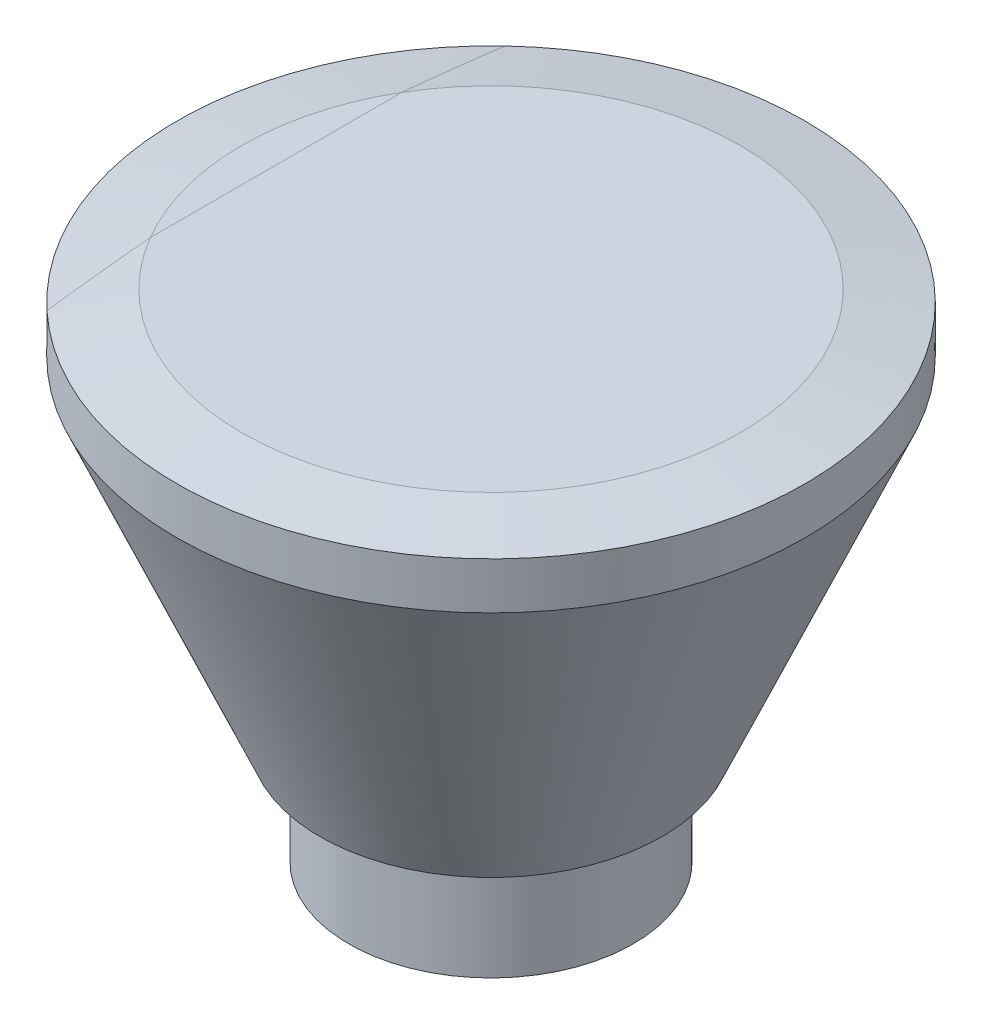
SolidWorks part; units mm, degrees
material "PLA"
ref_plane "Front Plane" through (0, 0, 0) normal (0, 0, 1) x (1, 0, 0)
ref_plane "Top Plane" through (0, 0, 0) normal (0, 1, 0) x (1, 0, 0)
ref_plane "Right Plane" through (0, 0, 0) normal (1, 0, 0) x (0, 0, -1)
sketch "Sketch1" plane through (0, 0, 0) normal (0, 0, 1) x (1, 0, 0)
  line L0 (-19, 22.4817) -> (-15.0608, 23.1763)
  line L2 (0, -1.5737) -> (0, 23.1763)
  line L3 (0, 23.1763) -> (-15.0608, 23.1763)
  line L4 (-19, 19.6513) -> (-19, 22.4817)
  line L6 (-5.6, 3.4263) -> (-3, 3.4263)
  line L12 (-8.6, -0.3237) -> (-8.6, -6.8237)
  line L13 (-8.6, -6.8237) -> (-5.6, -6.8237)
  line L14 (-5.6, -6.8237) -> (-5.6, 3.4263)
  line L15 (-10.35, 0.6763) -> (-10.35, -0.3237) construction
  line L16 (-10.35, -0.3237) -> (-8.6, -0.3237)
  line L20 (-3, 3.4263) -> (-3, -1.5737)
  line L21 (-3, -1.5737) -> (0, -1.5737)
  line L22 (-11.35, 0.6763) -> (-11.35, 1.6763) construction
  line L23 (-11.35, 1.6763) -> (-12.35, 1.6763) construction
  line L24 (-12.35, 1.6763) -> (-12.35, 2.6763) construction
  line L25 (-12.35, 2.6763) -> (-13.35, 2.6763) construction
  line L26 (-13.35, 2.6763) -> (-13.35, 3.6763) construction
  line L27 (-13.35, 3.6763) -> (-14.35, 3.6763) construction
  line L28 (-14.35, 3.6763) -> (-14.35, 4.6763) construction
  line L29 (-14.35, 4.6763) -> (-15.35, 4.6763) construction
  line L30 (-15.35, 4.6763) -> (-15.35, 5.6763) construction
  line L31 (-15.35, 5.6763) -> (-16.35, 5.6763) construction
  line L32 (-19, 19.6513) -> (-10.35, -0.3237)
  line L37 (-16.35, 5.6763) -> (-16.35, 3.6763) construction
  line L38 (-16.35, 3.6763) -> (-14.35, 3.6763) construction
  line L39 (-14.35, 3.6763) -> (-14.35, 1.6763) construction
  line L40 (-14.35, 1.6763) -> (-12.35, 1.6763) construction
  line L41 (-12.35, 1.6763) -> (-12.35, 0.6763)
  line L44 (-10.35, 0.6763) -> (-10.35, 0.8513) construction
  line L45 (-10.35, 0.8513) -> (-10.85, 0.8513) construction
  line L46 (-10.85, 0.8513) -> (-10.85, 2.0263) construction
  line L47 (-11.35, 2.0263) -> (-11.35, 3.2013) construction
  line L48 (-11.35, 3.2013) -> (-11.85, 3.2013) construction
  line L49 (-11.85, 3.2013) -> (-11.85, 4.3763) construction
  line L50 (-11.85, 4.3763) -> (-12.35, 4.3763) construction
  line L51 (-12.35, 4.3763) -> (-12.35, 5.5513) construction
  line L52 (-12.35, 5.5513) -> (-12.85, 5.5513) construction
  line L53 (-12.85, 5.5513) -> (-12.85, 6.7263) construction
  line L54 (-12.85, 6.7263) -> (-13.35, 6.7263) construction
  line L55 (-13.35, 6.7263) -> (-13.35, 7.9013) construction
  line L56 (-13.35, 7.9013) -> (-13.85, 7.9013) construction
  line L57 (-13.85, 7.9013) -> (-13.85, 9.0763) construction
  line L58 (-13.85, 9.0763) -> (-14.35, 9.0763) construction
  line L59 (-14.35, 9.0763) -> (-14.35, 10.2513) construction
  line L60 (-14.35, 10.2513) -> (-14.85, 10.2513) construction
  line L61 (-14.85, 10.2513) -> (-14.85, 11.4263) construction
  line L62 (-14.85, 11.4263) -> (-15.35, 11.4263) construction
  line L63 (-15.35, 11.4263) -> (-15.35, 12.6013) construction
  line L64 (-10.85, 2.0263) -> (-11.35, 2.0263) construction
  line L65 (-15.35, 12.6013) -> (-15.85, 12.6013) construction
  line L66 (-15.85, 12.6013) -> (-15.85, 13.7763) construction
  line L67 (-15.85, 13.7763) -> (-16.35, 13.7763) construction
  line L68 (-16.35, 13.7763) -> (-16.35, 14.9513) construction
  line L69 (-16.35, 14.9513) -> (-16.85, 14.9513) construction
  line L70 (-16.85, 14.9513) -> (-16.85, 16.1263) construction
  line L71 (-16.85, 16.1263) -> (-17.35, 16.1263) construction
  line L72 (-17.35, 16.1263) -> (-17.35, 17.3013) construction
  line L73 (-17.35, 17.3013) -> (-17.85, 17.3013) construction
  line L74 (-17.85, 17.3013) -> (-17.85, 18.4763) construction
  line L75 (-17.85, 18.4763) -> (-18.35, 18.4763) construction
  line L76 (-18.35, 18.4763) -> (-18.35, 19.6513) construction
  line L77 (-18.35, 19.6513) -> (-19, 19.6513) construction
  dimension "D6" = 4
  dimension "D7" = 10
  dimension "D1" = 5.6
  dimension "D4" = 19
  dimension "D10" = 1.75
  dimension "D2" = 10.25
  dimension "D8" = 6.5
  dimension "D11" = 3
  dimension "D12" = 5
  dimension "Bearing ID" = 8.6
  dimension "D3" = 30
  dimension "D9" = 0.175
  dimension "D13" = 0.5
  dimension "D14" = 1.175
revolve "Revolve1" add sketch "Sketch1" angle 360 about L2
sketch "Sketch3" plane through (0, -1.5737, 0) normal (0, -1, 0) x (1, 0, 0)
  circle A0 centre (0, 0) radius 3
extrude "Cut-Extrude1" cut sketch "Sketch3" against normal up to surface (5 mm away) up to face at (0, 3.4263, -3)
sketch "Sketch4" plane through (0, 23.1763, 0) normal (0, 1, 0) x (1, 0, 0)
  line L0 (-13, 13.8564) -> (-13, -13.8564)
  circle A0 centre (0, 0) radius 19 construction
  dimension "D1" = 13
split line "Split Line1"
sketch "Sketch5" plane through (0, 23.1763, 0) normal (0, 1, 0) x (1, 0, 0)
  line L0 (0, 0) -> (-13, 0)
  line L1 (-13, 7.6044) -> (-13, -7.6044) construction
equation "\"BearingID\"=8.6"
equation "\"Bearing ID@Sketch1\"=\"BearingID\""
